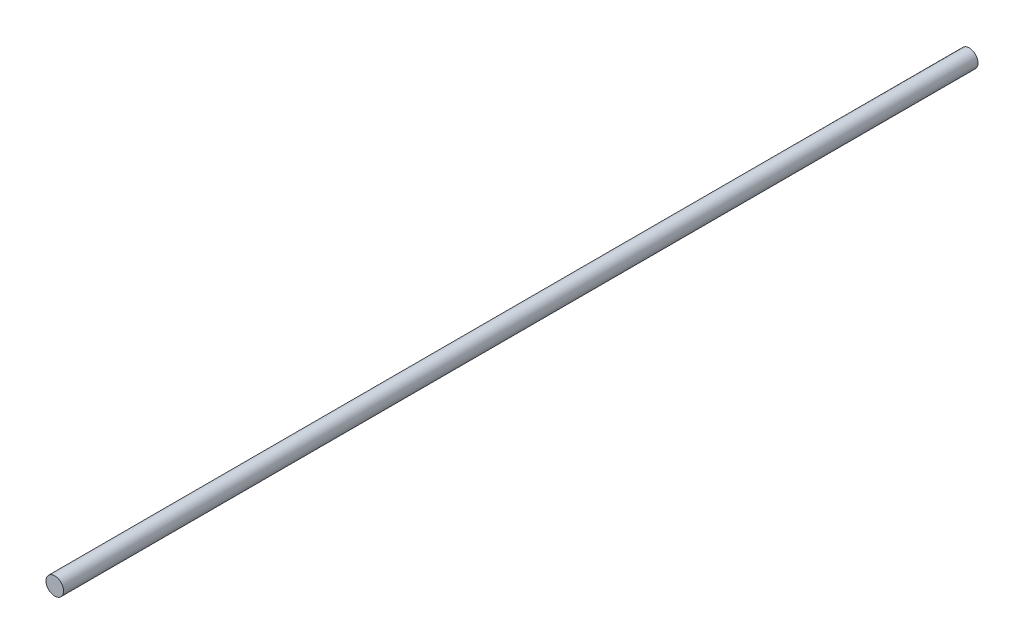
SolidWorks part; units mm, degrees
material "Plain Carbon Steel"
ref_plane "Front Plane" through (0, 0, 0) normal (0, 0, 1) x (1, 0, 0)
ref_plane "Top Plane" through (0, 0, 0) normal (0, 1, 0) x (1, 0, 0)
ref_plane "Right Plane" through (0, 0, 0) normal (1, 0, 0) x (0, 0, -1)
sketch "Sketch1" plane through (0, 0, 0) normal (0, 0, 1) x (1, 0, 0)
  circle A0 centre (0, 0) radius 6.35
  dimension "D1" = 12.7
extrude "Boss-Extrude1" add sketch "Sketch1" along normal mid plane 660.4
